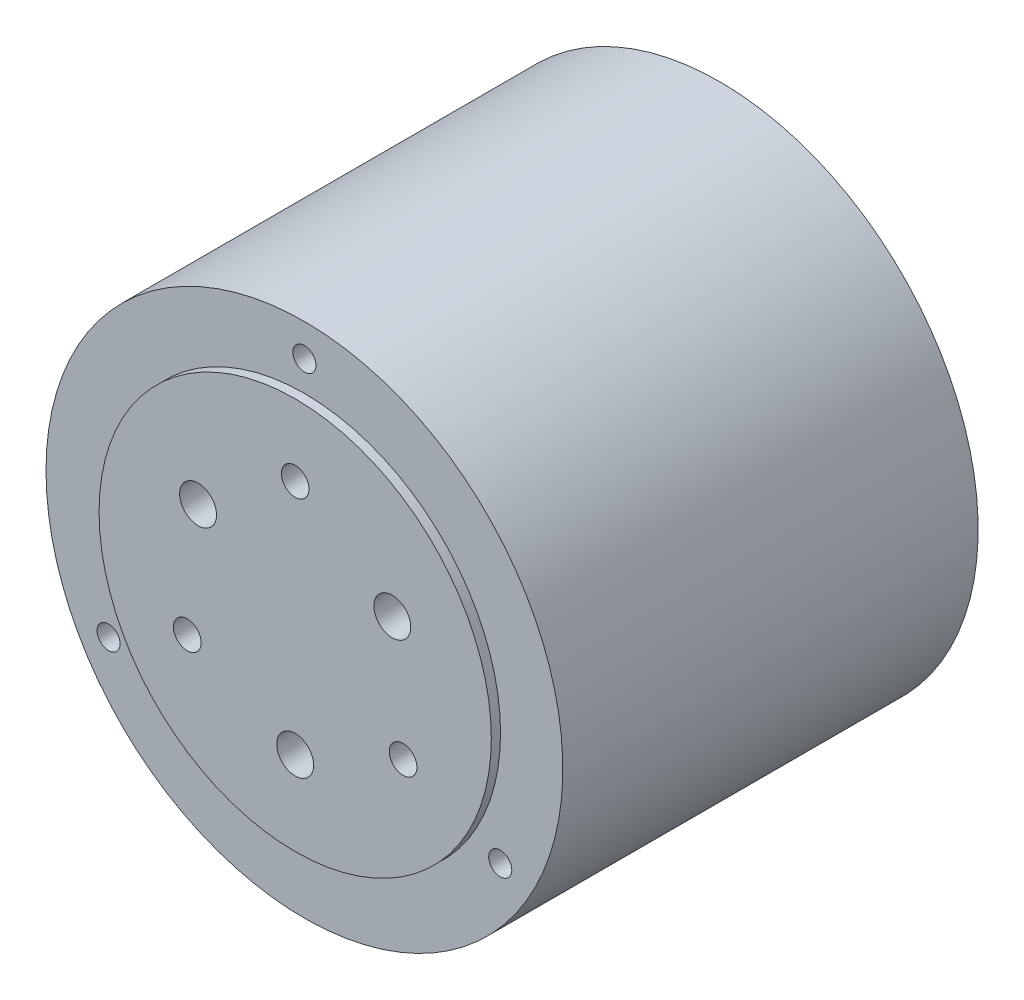
SolidWorks part; units mm, degrees
material "合金钢"
ref_plane "前视基准面" through (0, 0, 0) normal (0, 0, 1) x (1, 0, 0)
ref_plane "上视基准面" through (0, 0, 0) normal (0, 1, 0) x (1, 0, 0)
ref_plane "右视基准面" through (0, 0, 0) normal (1, 0, 0) x (0, 0, -1)
sketch "草图1" plane through (0, 0, 0) normal (0, 0, 1) x (1, 0, 0)
  circle A0 centre (0, 0) radius 28
  dimension "D1" = 56
extrude "凸台-拉伸1" add sketch "草图1" along normal blind 45
sketch "草图2" plane through (0, 0, 0) normal (0, 0, -1) x (-1, 0, 0)
  circle A0 centre (19, 0) radius 1.25
  circle A1 centre (0, 0) radius 19 construction
  circle A2 centre (0, -19) radius 1.25
  circle A3 centre (-19, 0) radius 1.25
  circle A4 centre (0, 19) radius 1.25
  point P13 (0, 0)
  dimension "D1" = 2.5
  dimension "D2" = 38
  dimension "D3" = 4
extrude "切除-拉伸1" cut sketch "草图2" against normal blind 4
sketch "草图3" plane through (0, 0, 45) normal (0, 0, 1) x (1, 0, 0)
  circle A0 centre (0, 0) radius 24.5 construction
  circle A1 centre (0, 24.5) radius 1.25
  circle A2 centre (21.2176, -12.25) radius 1.25
  circle A3 centre (-21.2176, -12.25) radius 1.25
  point P12 (0, 0)
  dimension "D1" = 49
  dimension "D2" = 2.5
  dimension "D3" = 3
extrude "切除-拉伸2" cut sketch "草图3" against normal blind 5
sketch "草图4" plane through (0, 0, 45) normal (0, 0, 1) x (1, 0, 0)
  circle A0 centre (0, 0) radius 21.25
  dimension "D1" = 42.5
extrude "凸台-拉伸2" add sketch "草图4" along normal blind 1
sketch "草图5" plane through (0, 0, 46) normal (0, 0, 1) x (1, 0, 0)
  circle A0 centre (0, 0) radius 13.5 construction
  circle A1 centre (0, 13.5) radius 1.5
  circle A2 centre (11.6913, -6.75) radius 1.5
  circle A3 centre (-11.6913, -6.75) radius 1.5
  point P12 (0, 0)
  dimension "D1" = 27
  dimension "D2" = 3
  dimension "D3" = 3
extrude "切除-拉伸3" cut sketch "草图5" against normal blind 5
sketch "草图6" plane through (0, 0, 46) normal (0, 0, 1) x (1, 0, 0)
  circle A0 centre (0, 0) radius 12.15 construction
  circle A1 centre (0, -12.15) radius 2
  circle A2 centre (-10.5222, 6.075) radius 2
  circle A3 centre (10.5222, 6.075) radius 2
  point P11 (0, 0)
  dimension "D1" = 24.3
  dimension "D2" = 4
  dimension "D3" = 3
extrude "切除-拉伸4" cut sketch "草图6" against normal blind 5
sketch "草图7" plane through (0, 0, 46) normal (0, 0, 1) x (1, 0, 0)
  circle A0 centre (0, 0) radius 12.15 construction
  circle A1 centre (0, 0) radius 13.5 construction
